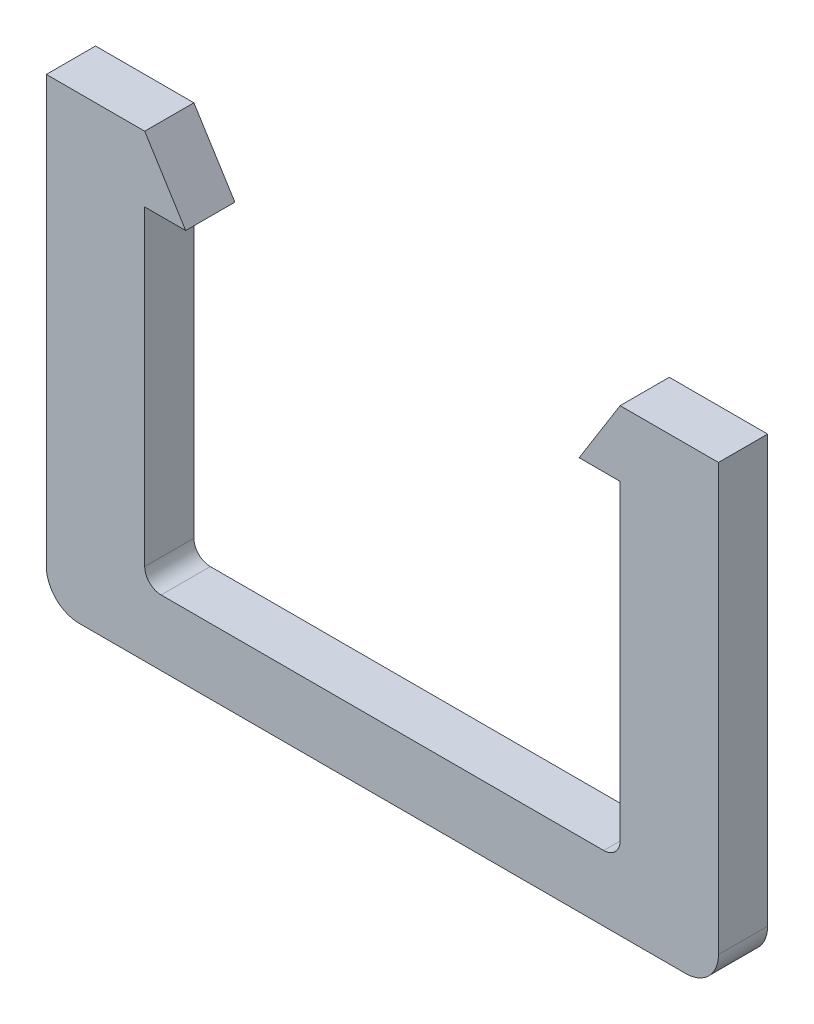
SolidWorks part; units mm, degrees
material "PLA"
ref_plane "Front Plane" through (0, 0, 0) normal (0, 0, 1) x (1, 0, 0)
ref_plane "Top Plane" through (0, 0, 0) normal (0, 1, 0) x (1, 0, 0)
ref_plane "Right Plane" through (0, 0, 0) normal (1, 0, 0) x (0, 0, -1)
sketch "Sketch1" plane through (0, 0, 0) normal (0, 0, 1) x (1, 0, 0)
  line L0 (-13.5, 4) -> (13.5, 4)
  line L1 (-14.5, 24) -> (-14.5, 5)
  line L2 (14.5, 5) -> (14.5, 24)
  line L3 (20.5, 2) -> (20.5, 28)
  line L4 (-20.5, 2) -> (-20.5, 28)
  line L6 (-14.5, 24) -> (-12, 24)
  line L9 (14.5, 24) -> (12, 24)
  line L12 (20.5, 28) -> (14.5, 28)
  line L13 (-20.5, 28) -> (-14.5, 28)
  line L14 (-14.5, 28) -> (-12, 24)
  line L15 (12, 24) -> (14.5, 28)
  line L18 (-18.5, 0) -> (18.5, 0)
  arc A1 (14.5, 5) -> (13.5, 4) centre (13.5, 5) cw
  arc A3 (-13.5, 4) -> (-14.5, 5) centre (-13.5, 5) cw
  arc A11 (20.5, 2) -> (18.5, 0) centre (18.5, 2) cw
  arc A12 (-18.5, 0) -> (-20.5, 2) centre (-18.5, 2) cw
  point P5 (-20.5, 0)
  point P6 (-20.2657, 0)
  point P7 (20.5, 0)
  point P10 (20.3541, 0)
  point P17 (14.5, 4)
  point P23 (-14.5, 4)
  dimension "D17" = 1
  dimension "D4" = 2
  dimension "D20" = 1
  dimension "D1" = 14.5
  dimension "D2" = 29
  dimension "D3" = 6
  dimension "D5" = 6
  dimension "D6" = 2.5
  dimension "D7" = 20
  dimension "D8" = 4
  dimension "D9" = 20
  dimension "D11" = 2.5
  dimension "D13" = 6
  dimension "D14" = 6
  dimension "D23" = 4
  dimension "D24" = 4
extrude "Boss-Extrude1" add sketch "Sketch1" along normal mid plane 3
